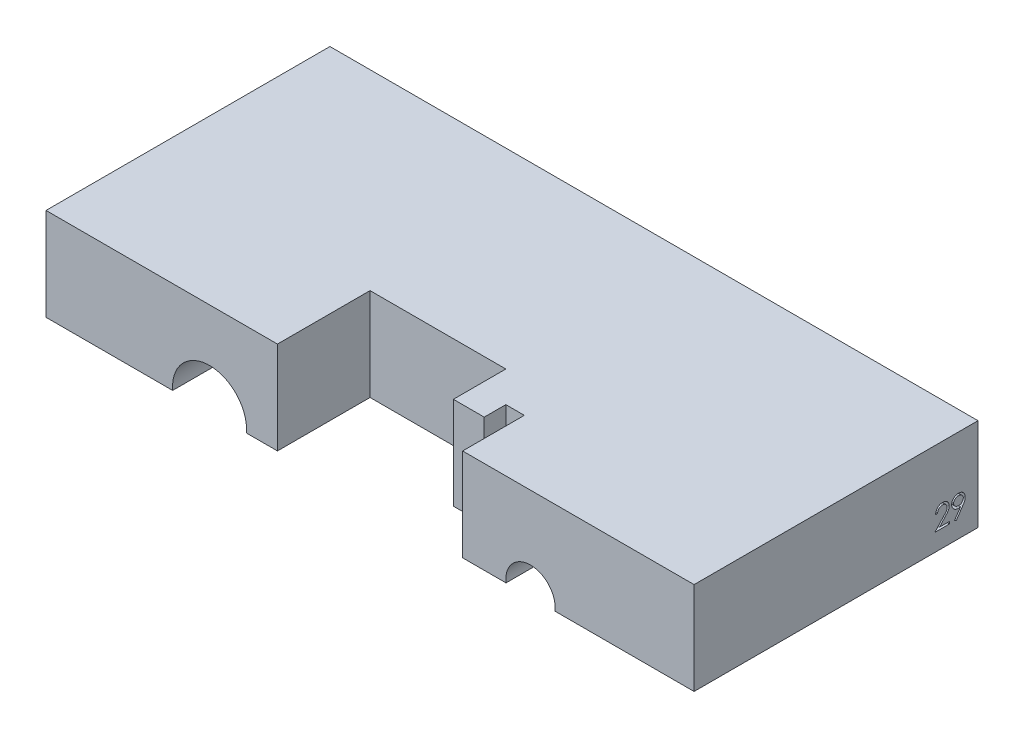
SolidWorks part; units mm, degrees
ref_plane "Front Plane" through (0, 0, 0) normal (0, 0, 1) x (1, 0, 0)
ref_plane "Top Plane" through (0, 0, 0) normal (0, 1, 0) x (1, 0, 0)
ref_plane "Right Plane" through (0, 0, 0) normal (1, 0, 0) x (0, 0, -1)
sketch "Sketch1" plane through (0, 0, 0) normal (0, 1, 0) x (1, 0, 0)
  line L1 (0, 0) -> (105, 0)
  line L2 (0, 0) -> (0, 92)
  line L3 (0, 92) -> (105, 92)
  line L4 (105, 0) -> (105, 92)
  dimension "D1" = 92
  dimension "D2" = 105
extrude "Boss-Extrude1" add sketch "Sketch1" along normal blind 15
sketch "Sketch2" plane through (0, 15, 0) normal (0, 1, 0) x (1, 0, 0)
  line L0 (0, 46) -> (105, 46) construction
  line L1 (0, 92) -> (0, 0) construction
  line L2 (105, 0) -> (105, 92) construction
  line L3 (52.5, 0) -> (52.5, 92) construction
  line L4 (0, 0) -> (105, 0) construction
  line L5 (105, 92) -> (0, 92) construction
  line L7 (67.5, 31) -> (37.5, 31)
  line L8 (67.5, 31) -> (67.5, 61)
  line L9 (67.5, 61) -> (37.5, 61)
  line L10 (37.5, 31) -> (37.5, 61)
  line L11 (67.5, 31) -> (37.5, 61) construction
  line L12 (67.5, 61) -> (37.5, 31) construction
  point P12 (52.5, 46)
  dimension "D1" = 30
  dimension "D2" = 30
extrude "Cut-Extrude1" cut sketch "Sketch2" against normal blind 72
ref_plane "Plane5" through (52.5, 0, 0) normal (-1, 0, 0) x (0, 0, 1)
ref_plane "Plane6" through (26.25, 0, 0) normal (-1, 0, 0) x (0, 0, 1)
ref_plane "Plane7" through (78.75, 0, 0) normal (-1, 0, 0) x (0, 0, 1)
ref_plane "Plane8" through (0, 0, -46) normal (0, 0, 1) x (1, 0, 0)
sketch "Sketch15" plane through (0, 15, 0) normal (0, 1, 0) x (1, 0, 0)
  line L0 (0, 46) -> (105, 46) construction
  line L1 (0, 92) -> (0, 0) construction
  line L2 (105, 0) -> (105, 92) construction
  line L4 (72.5, 67) -> (72.5, 46)
  line L5 (72.5, 46) -> (72.5, 25)
  line L7 (72.5, 67) -> (59.5, 67)
  line L8 (67.5, 61) -> (37.5, 61) construction
  line L9 (59.5, 61) -> (59.5, 52.5)
  line L10 (59.5, 52.5) -> (64.5, 52.5)
  line L11 (64.5, 52.5) -> (64.5, 56)
  line L12 (64.5, 56) -> (67.5, 56)
  line L13 (67.5, 31) -> (67.5, 61) construction
  line L15 (67.5, 36) -> (64.5, 36)
  line L16 (64.5, 36) -> (64.5, 39.5)
  line L17 (64.5, 39.5) -> (59.5, 39.5)
  line L18 (59.5, 39.5) -> (59.5, 31)
  line L19 (37.5, 31) -> (67.5, 31) construction
  line L21 (59.5, 67) -> (59.5, 61)
  line L22 (59.5, 31) -> (59.5, 25)
  line L23 (59.5, 25) -> (72.5, 25)
  line L25 (67.5, 56) -> (67.5, 46)
  line L26 (67.5, 46) -> (67.5, 36)
  dimension "D1" = 21
  dimension "D2" = 21
  dimension "D3" = 3
  dimension "D4" = 3
  dimension "D5" = 13
  dimension "D6" = 13
  dimension "D7" = 10
  dimension "D8" = 10
  dimension "D9" = 5
  dimension "D10" = 6.5
  dimension "D11" = 6.5
extrude "Boss-Extrude4" add sketch "Sketch15" against normal blind 15
sketch "Sketch18" plane through (0, 0, -46) normal (0, 0, 1) x (1, 0, 0)
  line L0 (52.5, 0.5) -> (52.5, 0) construction
  line L2 (37.5, 0) -> (59.5, 0) construction
  line L3 (0, 0.5) -> (74.5, 0.5) construction
  line L4 (52.5, 0) -> (52.5, 15) construction
  line L5 (0, 15) -> (105, 15) construction
  line L6 (105, 0) -> (0, 0) construction
  circle A0 centre (26.5, 0.5) radius 4
  circle A2 centre (78.5, 0.5) radius 4
  dimension "D2" = 8
  dimension "D4" = 8
  dimension "D1" = 0.5
  dimension "D3" = 26
  dimension "D5" = 26
extrude "Cut-Extrude2" cut sketch "Sketch18" against normal blind 64 and the other way blind 84
sketch "Sketch22" plane through (0, 0, -46) normal (0, 0, 1) x (1, 0, 0)
  circle A0 centre (26.5, 0.5) radius 6
  dimension "D1" = 12
extrude "Cut-Extrude3" cut sketch "Sketch22" against normal blind 10 and the other way blind 10
ref_plane "Plane9" through (0, 0, -69) normal (0, 0, -1) x (-1, 0, 0)
sketch "Sketch23" plane through (0, 0, -69) normal (0, 0, -1) x (-1, 0, 0)
  circle A0 centre (-78.5, 0.5) radius 6
  dimension "D1" = 12
extrude "Cut-Extrude4" cut sketch "Sketch23" against normal blind 10 and the other way blind 10
ref_plane "Plane10" through (0, 0, -23) normal (0, 0, 1) x (1, 0, 0)
sketch "Sketch24" plane through (0, 0, -23) normal (0, 0, 1) x (1, 0, 0)
  circle A0 centre (78.5, 0.5) radius 6
  dimension "D1" = 12
extrude "Cut-Extrude5" cut sketch "Sketch24" against normal blind 10 and the other way blind 10
sketch "Sketch27" plane through (0, 0, 0) normal (-1, 0, 0) x (0, 0, 1)
  text T0 "29"
extrude "Cut-Extrude7" cut sketch "Sketch27" against normal blind 2
sketch "Sketch28" plane through (105, 0, 0) normal (1, 0, 0) x (0, 0, -1)
  text T0 "29"
extrude "Cut-Extrude8" cut sketch "Sketch28" against normal blind 2
sketch "Sketch30" plane through (0, 0, 0) normal (0, -1, 0) x (1, 0, 0)
  line L0 (0, -46) -> (105, -46) construction
  line L1 (0, -92) -> (0, 0) construction
  line L2 (105, 0) -> (105, -92) construction
  line L4 (0, -46) -> (105, -46)
  line L5 (0, -46) -> (0, 0)
  line L6 (0, 0) -> (105, 0)
  line L7 (105, -46) -> (105, 0)
extrude "Cut-Extrude10" cut sketch "Sketch30" against normal blind 40
